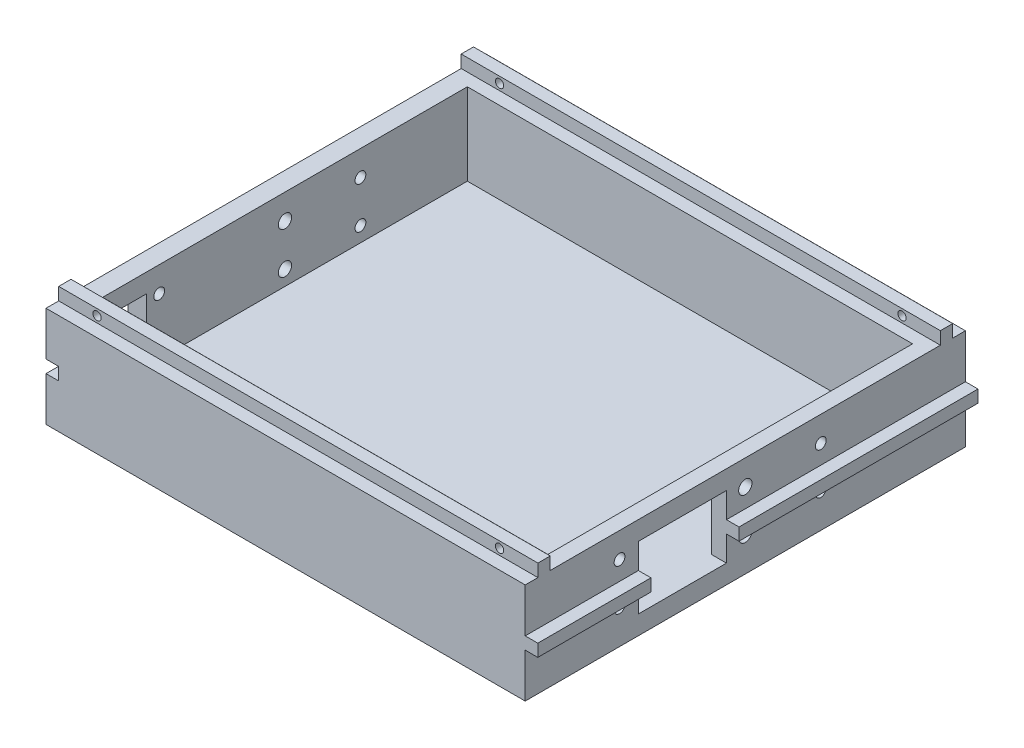
SolidWorks part; units mm, degrees
ref_plane "Front Plane" through (0, 0, 0) normal (0, 0, 1) x (1, 0, 0)
ref_plane "Top Plane" through (0, 0, 0) normal (0, 1, 0) x (1, 0, 0)
ref_plane "Right Plane" through (0, 0, 0) normal (1, 0, 0) x (0, 0, -1)
sketch "Sketch1" plane through (0, 0, 0) normal (0, 1, 0) x (1, 0, 0)
  line L1 (-95.25, 87.5) -> (95.25, 87.5)
  line L2 (-95.25, 87.5) -> (-95.25, -87.5)
  line L3 (-95.25, -87.5) -> (95.25, -87.5)
  line L4 (95.25, 87.5) -> (95.25, -87.5)
  line L5 (-95.25, 87.5) -> (95.25, -87.5) construction
  line L6 (-95.25, -87.5) -> (95.25, 87.5) construction
  point P0 (0, 0)
  dimension "D1" = 175
  dimension "D2" = 190.5
extrude "Boss-Extrude1" add sketch "Sketch1" along normal blind 40
shell "Shell1" thickness 15
sketch "Sketch2" plane through (95.25, 0, 0) normal (1, 0, 0) x (0, 0, -1)
  line L0 (-87.5, 20) -> (87.5, 20) construction
  line L1 (-87.5, 40) -> (-87.5, 0) construction
  line L2 (87.5, 40) -> (87.5, 0) construction
  line L4 (-87.5, 22.45) -> (87.5, 22.45)
  line L5 (-87.5, 22.45) -> (-87.5, 17.55)
  line L6 (-87.5, 17.55) -> (87.5, 17.55)
  line L7 (87.5, 22.45) -> (87.5, 17.55)
  line L8 (-87.5, 22.45) -> (87.5, 17.55) construction
  line L9 (-87.5, 17.55) -> (87.5, 22.45) construction
  point P6 (0, 20)
  dimension "D1" = 4.9
extrude "Boss-Extrude2" add sketch "Sketch2" along normal blind 5
sketch "Sketch3" plane through (0, 0, 87.5) normal (0, 0, 1) x (1, 0, 0)
  line L0 (-95.25, 40) -> (-95.25, 0) construction
  line L1 (-95.25, 22.5) -> (-90.25, 22.5)
  line L3 (-95.25, 17.5) -> (-90.25, 17.5)
  line L4 (-90.25, 22.5) -> (-90.25, 17.5)
  line L7 (-95.25, 22.5) -> (-95.25, 17.5)
  point P0 (-95.25, 20)
  point P2 (-95.25, 20)
  dimension "D1" = 5
  dimension "D2" = 5
extrude "Cut-Extrude1" cut sketch "Sketch3" against normal up to surface (175 mm away) up to face at (48.875, 20, -87.5)
sketch "Sketch4" plane through (0, 40, 0) normal (0, 1, 0) x (1, 0, 0)
  line L0 (80.25, 72.5) -> (-80.25, 72.5) construction
  line L1 (-80.25, -72.5) -> (-87.75, -72.5)
  line L2 (-80.25, -72.5) -> (-80.25, 72.5)
  line L3 (-80.25, 72.5) -> (-87.75, 72.5)
  line L4 (-87.75, -72.5) -> (-87.75, 72.5)
  dimension "D1" = 7.5
extrude "Cut-Extrude2" cut sketch "Sketch4" against normal up to surface (25 mm away) up to face at (0, 15, 0)
sketch "Sketch5" plane through (-95.25, 0, 0) normal (-1, 0, 0) x (0, 0, 1)
  line L0 (-87.5, 30) -> (87.5, 30) construction
  line L1 (-87.5, 40) -> (-87.5, 22.5) construction
  line L3 (-87.5, 20) -> (87.5, 20) construction
  line L4 (-87.5, 22.5) -> (-87.5, 17.5) construction
  line L5 (87.5, 17.5) -> (87.5, 22.5) construction
  line L6 (87.5, 40) -> (87.5, 22.5) construction
  line L7 (-87.5, 13.5) -> (87.5, 13.5) construction
  line L8 (-87.5, 17.5) -> (-87.5, 0) construction
  line L9 (87.5, 17.5) -> (87.5, 0) construction
  circle A0 centre (0, 30) radius 2.65
  circle A1 centre (-30, 30) radius 2.15
  circle A2 centre (50, 30) radius 2.15
  circle A6 centre (-30, 13.5) radius 2.15
  circle A7 centre (0, 13.5) radius 2.65
  circle A8 centre (50, 13.5) radius 2.15
  point P28 (0, 30)
  dimension "D1" = 5.3
  dimension "D2" = 4.3
  dimension "D3" = 4.3
  dimension "D6" = 5.3
  dimension "D7" = 4.3
  dimension "D8" = 4.3
  dimension "D4" = 30
  dimension "D5" = 50
  dimension "D9" = 6.5
  dimension "D10" = 10
  dimension "D11" = 30
  dimension "D12" = 50
extrude "Cut-Extrude3" cut sketch "Sketch5" against normal up to surface (183 mm away)
sketch "Sketch6" plane through (0, 15, 0) normal (0, 1, 0) x (1, 0, 0)
  line L0 (-87.75, 72.5) -> (80.25, 72.5)
  line L1 (80.25, 72.5) -> (80.25, -72.5)
  line L2 (80.25, -72.5) -> (-87.75, -72.5)
  line L3 (-87.75, -72.5) -> (-87.75, 72.5)
extrude "Cut-Extrude4" cut sketch "Sketch6" against normal blind 7.5
mirror "Mirror1" about plane through (0, 0, 0) normal (1, 0, 0) of "Cut-Extrude3"
sketch "Sketch7" plane through (0, 40, 0) normal (0, 1, 0) x (1, 0, 0)
  line L1 (80.25, 72.5) -> (89.25, 72.5)
  line L2 (80.25, 72.5) -> (80.25, -72.4962)
  line L3 (80.25, -72.4962) -> (89.25, -72.4962)
  line L4 (89.25, 72.5) -> (89.25, -72.4962)
  dimension "D1" = 9
extrude "Cut-Extrude5" cut sketch "Sketch7" against normal up to surface (32.5 mm away) up to face at (-3.75, 7.5, 0)
sketch "Sketch9" plane through (0, 0, 87.5) normal (0, 0, 1) x (1, 0, 0)
  line L0 (95.25, 40) -> (95.25, 22.45) construction
  line L1 (-95.25, 40) -> (95.25, 40)
  line L2 (-95.25, 40) -> (-95.25, 45)
  line L3 (-95.25, 45) -> (95.25, 45)
  line L4 (95.25, 40) -> (95.25, 45)
  dimension "D1" = 5
extrude "Boss-Extrude3" add sketch "Sketch9" along normal mid plane 4.9 from offset 7.5 offset against normal yes
sketch "Sketch11" plane through (0, 0, 77.55) normal (0, 0, -1) x (-1, 0, 0)
  line L0 (-95.25, 42.5) -> (95.25, 42.5) construction
  line L1 (-95.25, 40) -> (-95.25, 45) construction
  line L2 (95.25, 45) -> (95.25, 40) construction
  circle A0 centre (-80, 42.5) radius 1.65
  circle A1 centre (80, 42.5) radius 1.65
  dimension "D3" = 3.3
  dimension "D1" = 80
  dimension "D2" = 80
extrude "Cut-Extrude7" cut sketch "Sketch11" against normal up to surface (4.9 mm away) up to face at (0, 42.5, 82.45)
mirror "Mirror2" about plane through (0, 0, 0) normal (0, 0, 1) of "Cut-Extrude7", "Boss-Extrude3"
sketch "Sketch12" plane through (-87.75, 0, 0) normal (1, 0, 0) x (0, 0, -1)
  line L0 (-25, 40) -> (-25, 0) construction
  line L1 (-77.55, 40) -> (77.55, 40) construction
  line L2 (-87.5, 0) -> (87.5, 0) construction
  line L4 (-42.5, 32.5) -> (-7.5, 32.5)
  line L5 (-42.5, 32.5) -> (-42.5, 7.5)
  line L6 (-42.5, 7.5) -> (-7.5, 7.5)
  line L7 (-7.5, 32.5) -> (-7.5, 7.5)
  line L8 (-42.5, 32.5) -> (-7.5, 7.5) construction
  line L9 (-42.5, 7.5) -> (-7.5, 32.5) construction
  circle A0 centre (-50, 30) radius 2.15 construction
  point P8 (-25, 20)
  dimension "D1" = 25
  dimension "D2" = 35
  dimension "D3" = 25
extrude "Cut-Extrude8" cut sketch "Sketch12" along normal through all
sketch "Sketch13" plane through (-87.75, 0, 0) normal (1, 0, 0) x (0, 0, -1)
  line L0 (-62.5, 40) -> (-62.5, 0) construction
  line L1 (-77.55, 40) -> (77.55, 40) construction
  line L2 (-87.5, 0) -> (87.5, 0) construction
  line L4 (-70, 32.5) -> (-55, 32.5)
  line L5 (-70, 32.5) -> (-70, 7.5)
  line L6 (-70, 7.5) -> (-55, 7.5)
  line L7 (-55, 32.5) -> (-55, 7.5)
  line L8 (-70, 32.5) -> (-55, 7.5) construction
  line L9 (-70, 7.5) -> (-55, 32.5) construction
  circle A0 centre (-50, 13.5) radius 2.15 construction
  point P9 (-62.5, 20)
  dimension "D1" = 12.5
  dimension "D2" = 15
  dimension "D3" = 25
extrude "Cut-Extrude9" cut sketch "Sketch13" against normal up to surface (7.5 mm away) up to face at (-95.25, 13.5, -27.85)
